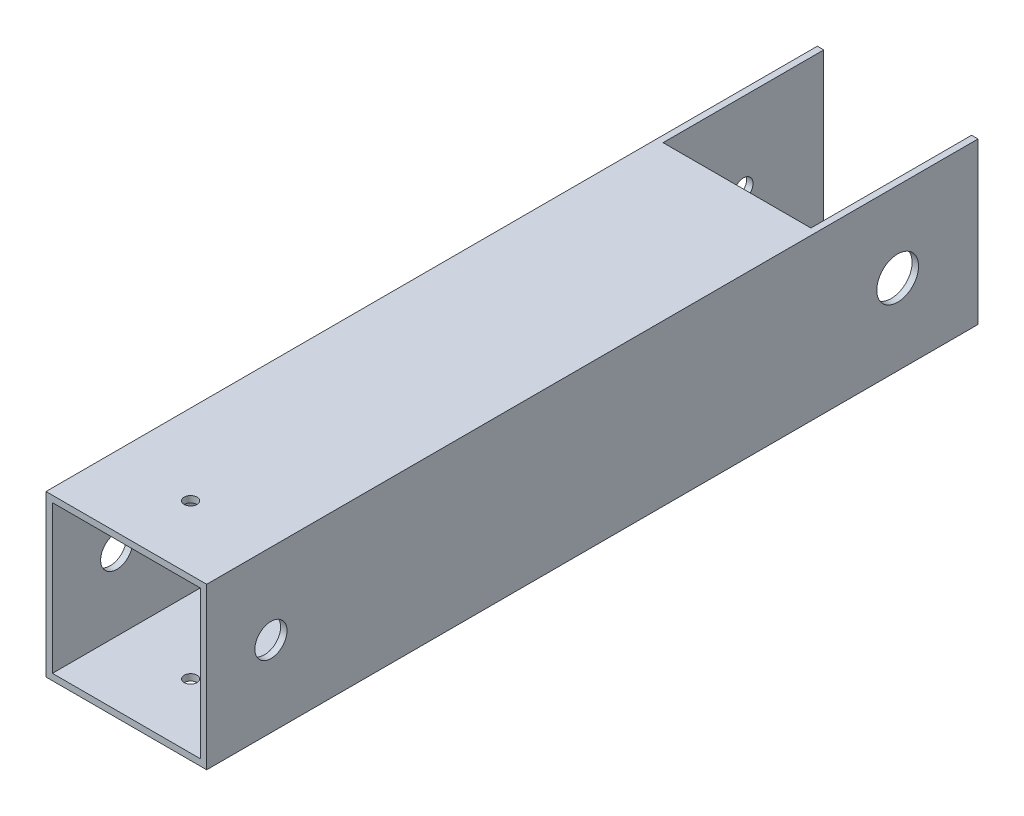
SolidWorks part; units mm, degrees
material "6061 Alloy"
ref_plane "Front Plane" through (0, 0, 0) normal (0, 0, 1) x (1, 0, 0)
ref_plane "Top Plane" through (0, 0, 0) normal (0, 1, 0) x (1, 0, 0)
ref_plane "Right Plane" through (0, 0, 0) normal (1, 0, 0) x (0, 0, -1)
sketch "Sketch1" plane through (0, 0, 0) normal (0, 0, 1) x (1, 0, 0)
  line L1 (-25, -25) -> (25, -25)
  line L2 (-25, -25) -> (-25, 25)
  line L3 (-25, 25) -> (25, 25)
  line L4 (25, -25) -> (25, 25)
  line L5 (-25, -25) -> (25, 25) construction
  line L6 (-25, 25) -> (25, -25) construction
  line L7 (-23, -23) -> (23, -23)
  line L8 (-23, -23) -> (-23, 23)
  line L9 (-23, 23) -> (23, 23)
  line L10 (23, -23) -> (23, 23)
  line L11 (-23, -23) -> (23, 23) construction
  line L12 (-23, 23) -> (23, -23) construction
  point P0 (0, 0)
  point P6 (0, 0)
  dimension "D1" = 50
  dimension "D2" = 2
  dimension "D3" = 2
extrude "Boss-Extrude1" add sketch "Sketch1" against normal blind 240
sketch "Sketch2" plane through (0, 25, 0) normal (0, 1, 0) x (1, 0, 0)
  line L0 (25, 240) -> (-25, 240) construction
  line L1 (23, 190) -> (-23, 190)
  line L2 (23, 190) -> (23, 240)
  line L3 (23, 240) -> (-23, 240)
  line L4 (-23, 190) -> (-23, 240)
  line L5 (23, 190) -> (-23, 240) construction
  line L6 (23, 240) -> (-23, 190) construction
  line L7 (-25, 240) -> (-25, 0) construction
  line L8 (25, 240) -> (25, 0) construction
  point P0 (0, 215)
  dimension "D1" = 2
  dimension "D2" = 2
  dimension "D3" = 50
extrude "Cut-Extrude1" cut sketch "Sketch2" against normal through all
sketch "Sketch3" plane through (25, 0, 0) normal (1, 0, 0) x (0, 0, -1)
  line L0 (240, -25) -> (240, 25) construction
  line L2 (0, -25) -> (0, 25) construction
  circle A0 centre (215, 0) radius 6.5
  circle A1 centre (20, 0) radius 5
  point P9 (0, 0)
  dimension "D1" = 13
  dimension "D3" = 10
  dimension "D2" = 25
  dimension "D4" = 20
extrude "Cut-Extrude2" cut sketch "Sketch3" against normal up to next
sketch "Sketch4" plane through (-25, 0, 0) normal (-1, 0, 0) x (0, 0, 1)
  circle A0 centre (-215, 0) radius 6.5 construction
  circle A1 centre (-20, 0) radius 5 construction
  circle A2 centre (-215, 0) radius 6.5 construction
  circle A3 centre (-20, 0) radius 5 construction
  circle A4 centre (-215, 0) radius 3
  circle A5 centre (-20, 0) radius 5
  dimension "D1" = 6
  dimension "D2" = 10
extrude "Cut-Extrude3" cut sketch "Sketch4" against normal up to next
sketch "Sketch5" plane through (-25, 0, 0) normal (1, 0, 0) x (0, 0, -1)
  line L0 (55, 23) -> (55, -23)
  line L2 (55, -23) -> (175, -23)
  line L3 (175, -23) -> (175, 23)
  line L4 (175, 23) -> (55, 23)
  line L5 (240, -25) -> (0, -25) construction
  line L6 (0, -25) -> (0, 25) construction
  line L9 (240, 25) -> (0, 25) construction
  dimension "D1" = 2
  dimension "D2" = 55
  dimension "D3" = 120
  dimension "D4" = 2
extrude "Cut-Extrude5" cut sketch "Sketch5" along normal blind 48
sketch "Sketch6" plane through (0, 25, 0) normal (0, 1, 0) x (1, 0, 0)
  line L0 (25, 0) -> (-25, 0) construction
  circle A0 centre (0, 20) radius 2
  point P4 (0, 0)
  dimension "D2" = 4
  dimension "D1" = 20
extrude "Cut-Extrude6" cut sketch "Sketch6" against normal through all
